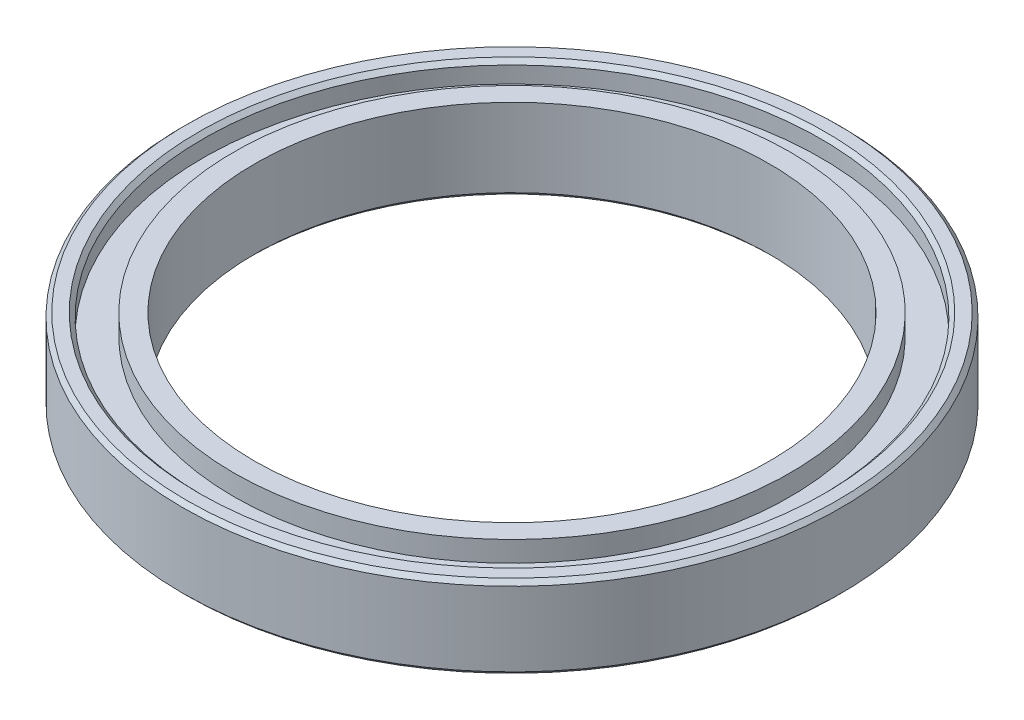
SolidWorks part; units mm, degrees
ref_plane "Front Plane" through (0, 0, 0) normal (0, 0, 1) x (1, 0, 0)
ref_plane "Top Plane" through (0, 0, 0) normal (0, 1, 0) x (1, 0, 0)
ref_plane "Right Plane" through (0, 0, 0) normal (1, 0, 0) x (0, 0, -1)
sketch "Sketch1" plane through (0, 0, 0) normal (0, 1, 0) x (1, 0, 0)
  circle A0 centre (0, 0) radius 16
  circle A1 centre (0, 0) radius 12.5
  dimension "D1" = 32
  dimension "D2" = 25
extrude "Boss-Extrude1" add sketch "Sketch1" along normal blind 4
sketch "Sketch2" plane through (0, 4, 0) normal (0, 1, 0) x (1, 0, 0)
  circle A0 centre (0, 0) radius 15
  circle A1 centre (0, 0) radius 13.5
  dimension "D1" = 27
  dimension "D2" = 30
extrude "Cut-Extrude1" cut sketch "Sketch2" against normal blind 1
sketch "Sketch3" plane through (0, 0, 0) normal (0, -1, 0) x (1, 0, 0)
  circle A0 centre (0, 0) radius 13.5
  circle A1 centre (0, 0) radius 15
  dimension "D1" = 30
  dimension "D2" = 27
extrude "Cut-Extrude2" cut sketch "Sketch3" against normal blind 1
chamfer "Chamfer1" distance 0.2 angle 45 6 edges at (0, 4, 15) (0, 4, 16) (0, 0, 16) (0, 0, -15) (0, 0, -13.5) (0, 0, 12.5)
